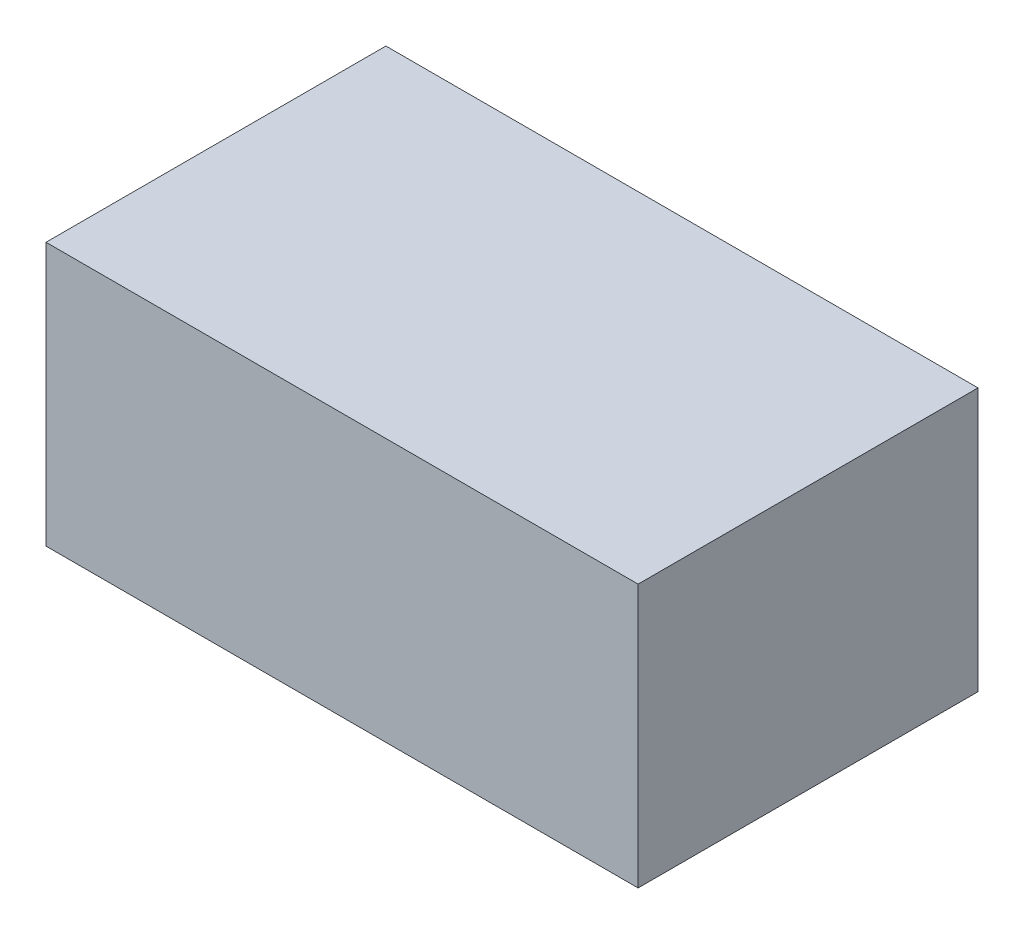
SolidWorks part; units mm, degrees
ref_plane "Front Plane" through (0, 0, 0) normal (0, 0, 1) x (1, 0, 0)
ref_plane "Top Plane" through (0, 0, 0) normal (0, 1, 0) x (1, 0, 0)
ref_plane "Right Plane" through (0, 0, 0) normal (1, 0, 0) x (0, 0, -1)
sketch "Sketch1" plane through (0, 0, 0) normal (0, 1, 0) x (1, 0, 0)
  line L1 (-342.9, -196.85) -> (342.9, -196.85)
  line L2 (-342.9, -196.85) -> (-342.9, 196.85)
  line L3 (-342.9, 196.85) -> (342.9, 196.85)
  line L4 (342.9, -196.85) -> (342.9, 196.85)
  line L5 (-342.9, -196.85) -> (342.9, 196.85) construction
  line L6 (-342.9, 196.85) -> (342.9, -196.85) construction
  point P0 (0, 0)
  dimension "D1" = 393.7
  dimension "D2" = 685.8
extrude "Boss-Extrude1" add sketch "Sketch1" along normal blind 304.8 contours L2 L1 L4 L3
